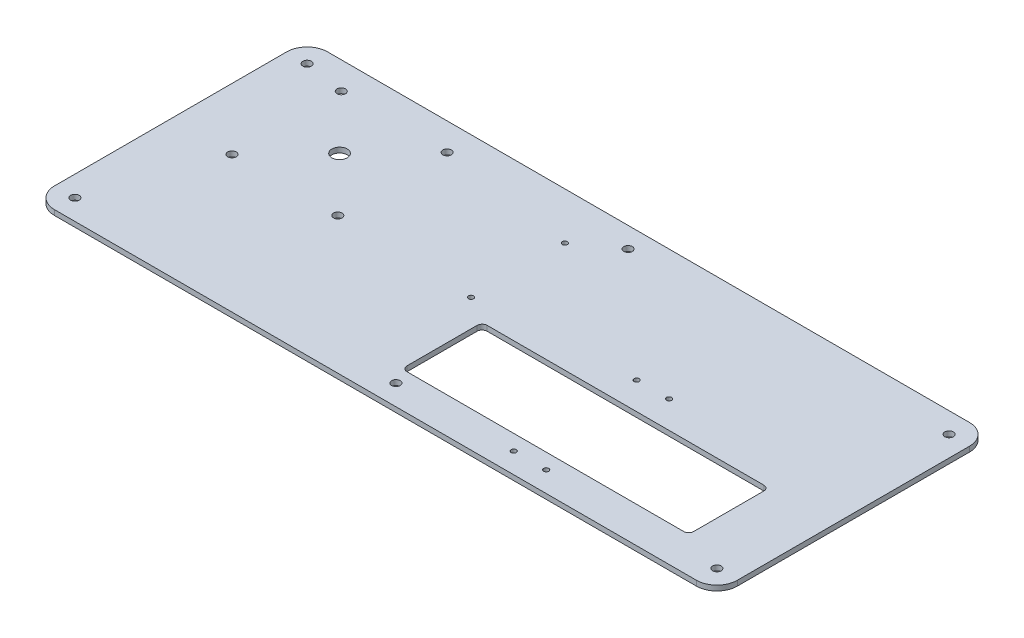
SolidWorks part; units mm, degrees
material "AISI 1020"
ref_plane "Front Plane" through (0, 0, 0) normal (0, 0, 1) x (1, 0, 0)
ref_plane "Top Plane" through (0, 0, 0) normal (0, 1, 0) x (1, 0, 0)
ref_plane "Right Plane" through (0, 0, 0) normal (1, 0, 0) x (0, 0, -1)
sketch "Sketch1" plane through (0, 0, 0) normal (0, 1, 0) x (1, 0, 0)
  line L1 (-188, -80) -> (188, -80)
  line L2 (-200, -68) -> (-200, 68)
  line L3 (-188, 80) -> (188, 80)
  line L4 (200, -68) -> (200, 68)
  line L5 (-200, -80) -> (200, 80) construction
  line L6 (-200, 80) -> (200, -80) construction
  line L7 (-2.5, -59) -> (159.5, -59)
  line L8 (-5.5, -56) -> (-5.5, -15)
  line L9 (-2.5, -12) -> (159.5, -12)
  line L10 (162.5, -56) -> (162.5, -15)
  line L11 (-5.5, -59) -> (162.5, -12) construction
  line L12 (-5.5, -12) -> (162.5, -59) construction
  arc A0 (188, 80) -> (200, 68) centre (188, 68) cw
  arc A1 (188, -80) -> (200, -68) centre (188, -68) ccw
  arc A2 (-188, -80) -> (-200, -68) centre (-188, -68) cw
  arc A3 (-200, 68) -> (-188, 80) centre (-188, 68) cw
  arc A4 (-2.5, -59) -> (-5.5, -56) centre (-2.5, -56) cw
  arc A5 (159.5, -59) -> (162.5, -56) centre (159.5, -56) ccw
  arc A6 (159.5, -12) -> (162.5, -15) centre (159.5, -15) cw
  arc A7 (-5.5, -15) -> (-2.5, -12) centre (-2.5, -15) cw
  circle A8 centre (-188, 68) radius 2.5
  circle A9 centre (0, 68) radius 2.5
  circle A10 centre (188, 68) radius 2.5
  circle A11 centre (188, -68) radius 2.5
  circle A12 centre (0, -68) radius 2.5
  circle A13 centre (-188, -68) radius 2.5
  circle A14 centre (-21.5, 52.5) radius 1.5
  circle A15 centre (-21.5, -2.5) radius 1.5
  circle A16 centre (69, 4) radius 1.5
  circle A17 centre (88, 4) radius 1.5
  circle A18 centre (69, -68) radius 1.5
  circle A19 centre (88, -68) radius 1.5
  circle A20 centre (-133, 32) radius 4.5
  circle A21 centre (-164, 64) radius 2.5
  circle A22 centre (-102, 64) radius 2.5
  circle A23 centre (-102, 0) radius 2.5
  circle A24 centre (-164, 0) radius 2.5
  point P0 (0, 0)
  point P18 (78.5, -35.5)
  dimension "D1" = 12
  dimension "D4" = 3
  dimension "D9" = 5
  dimension "D13" = 188
  dimension "D14" = 3
  dimension "D16" = 55
  dimension "D18" = 19
  dimension "D21" = 72
  dimension "D22" = 9
  dimension "D25" = 5
  dimension "D2" = 136
  dimension "D3" = 200
  dimension "D5" = 21
  dimension "D6" = 37.5
  dimension "D7" = 47
  dimension "D8" = 168
  dimension "D10" = 188
  dimension "D11" = 12
  dimension "D12" = 12
  dimension "D15" = 27.5
  dimension "D17" = 21.5
  dimension "D19" = 112
  dimension "D20" = 12
  dimension "D23" = 67
  dimension "D24" = 48
  dimension "D26" = 31
  dimension "D27" = 31
  dimension "D28" = 32
  dimension "D29" = 32
extrude "Boss-Extrude1" add sketch "Sketch1" along normal blind 3
